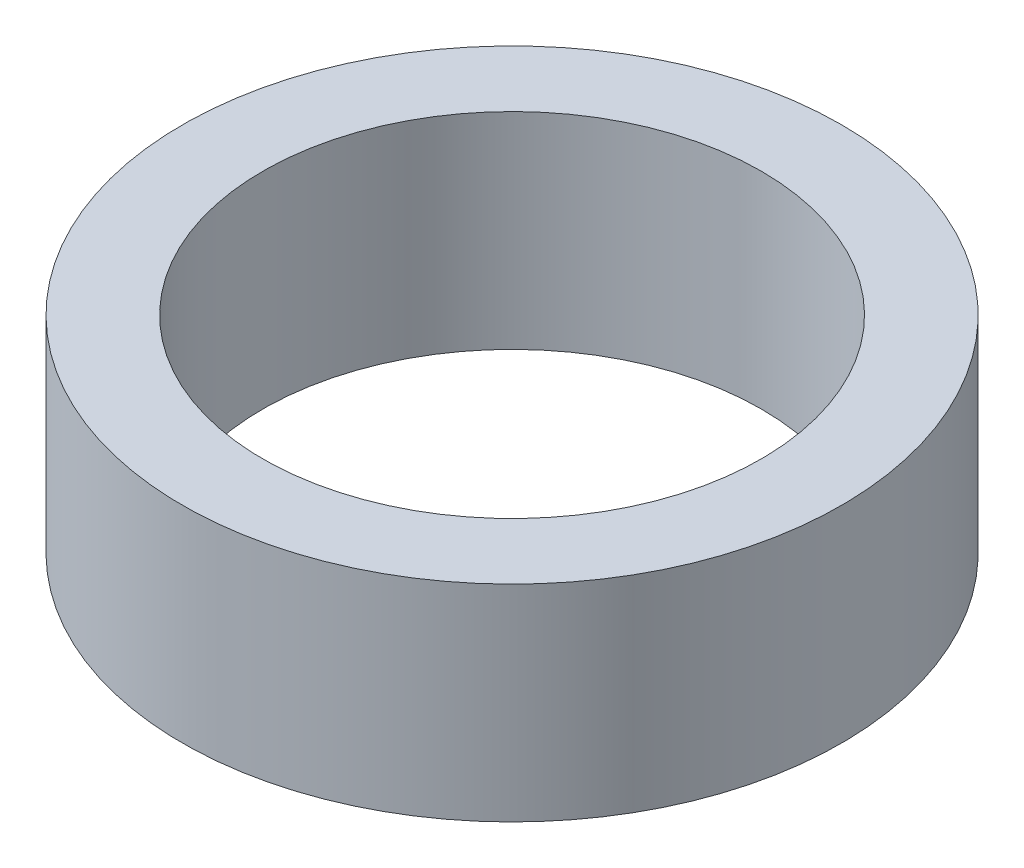
SolidWorks part; units mm, degrees
ref_plane "前视基准面" through (0, 0, 0) normal (0, 0, 1) x (1, 0, 0)
ref_plane "上视基准面" through (0, 0, 0) normal (0, 1, 0) x (1, 0, 0)
ref_plane "右视基准面" through (0, 0, 0) normal (1, 0, 0) x (0, 0, -1)
other "Configuration Table"
sketch "草图1" plane through (0, 0, 0) normal (0, 0, 1) x (1, 0, 0)
  line L0 (6.05, 0) -> (8, 0)
  line L1 (8, 0) -> (8, 5)
  line L2 (8, 5) -> (6.05, 5)
  line L3 (6.05, 5) -> (6.05, 0)
  line L4 (0, 0) -> (0, 5) construction
  dimension "x0" = 6.05
  dimension "x1" = 8
  dimension "y2" = 5
  dimension "y5" = 5
revolve "Rotary_seal_envelope" add sketch "草图1" angle 360 about L4
